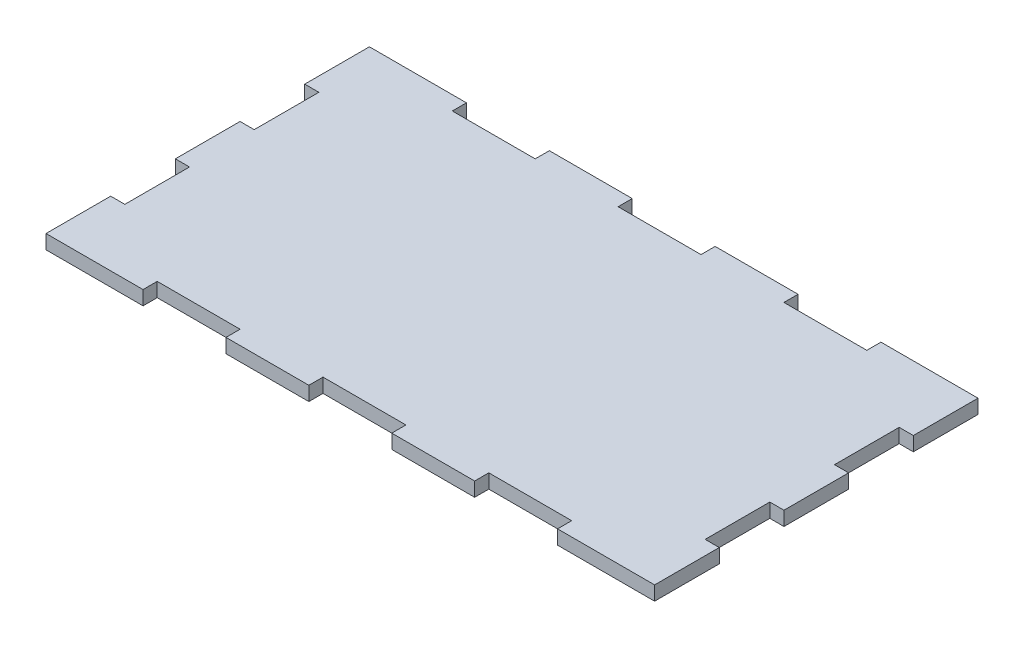
SolidWorks part; units mm, degrees
ref_plane "Front Plane" through (0, 0, 0) normal (0, 0, 1) x (1, 0, 0)
ref_plane "Top Plane" through (0, 0, 0) normal (0, 1, 0) x (1, 0, 0)
ref_plane "Right Plane" through (0, 0, 0) normal (1, 0, 0) x (0, 0, -1)
sketch "Sketch1" plane through (0, 0, 0) normal (0, 1, 0) x (1, 0, 0)
  line L1 (-215.1, 114.3) -> (-146.5, 114.3)
  line L2 (-215.1, 114.3) -> (-215.1, 68.58)
  line L4 (215.1, 114.3) -> (215.1, 68.58)
  line L5 (-215.1, -114.3) -> (-205.1, -114.3)
  line L6 (-205.1, -114.3) -> (-146.5, -114.3)
  line L7 (205.1, 68.58) -> (205.1, 22.86)
  line L9 (-205.1, 68.58) -> (-205.1, 22.86)
  line L11 (146.5, 104.3) -> (146.5, 114.3)
  line L12 (87.9, 104.3) -> (87.9, 114.3)
  line L13 (29.3, 104.3) -> (29.3, 114.3)
  line L14 (-29.3, 104.3) -> (-29.3, 114.3)
  line L15 (-87.9, 104.3) -> (-87.9, 114.3)
  line L16 (-146.5, 104.3) -> (-146.5, 114.3)
  line L17 (-215.1, -68.58) -> (-215.1, -114.3)
  line L18 (205.1, -22.86) -> (205.1, -68.58)
  line L20 (146.5, -104.3) -> (146.5, -114.3)
  line L21 (87.9, -104.3) -> (87.9, -114.3)
  line L22 (29.3, -104.3) -> (29.3, -114.3)
  line L23 (-29.3, -104.3) -> (-29.3, -114.3)
  line L24 (-87.9, -104.3) -> (-87.9, -114.3)
  line L25 (-146.5, -104.3) -> (-146.5, -114.3)
  line L26 (215.1, -114.3) -> (205.1, -114.3)
  line L27 (146.5, -114.3) -> (205.1, -114.3)
  line L28 (-205.1, -104.3) -> (205.1, -104.3) construction
  line L29 (87.9, -104.3) -> (146.5, -104.3)
  line L31 (-215.1, -114.3) -> (215.1, -114.3) construction
  line L32 (29.3, -114.3) -> (87.9, -114.3)
  line L33 (-29.3, -104.3) -> (29.3, -104.3)
  line L34 (-87.9, -114.3) -> (-29.3, -114.3)
  line L35 (-146.5, -104.3) -> (-87.9, -104.3)
  line L36 (215.1, -68.58) -> (205.1, -68.58)
  line L37 (215.1, -22.86) -> (205.1, -22.86)
  line L38 (-205.1, 104.3) -> (205.1, 104.3) construction
  line L39 (146.5, 114.3) -> (215.1, 114.3)
  line L40 (-215.1, 114.3) -> (215.1, 114.3) construction
  line L41 (29.3, 114.3) -> (87.9, 114.3)
  line L42 (-87.9, 114.3) -> (-29.3, 114.3)
  line L43 (-146.5, 104.3) -> (-87.9, 104.3)
  line L44 (-29.3, 104.3) -> (29.3, 104.3)
  line L45 (87.9, 104.3) -> (146.5, 104.3)
  line L46 (215.1, 22.86) -> (205.1, 22.86)
  line L47 (215.1, 68.58) -> (205.1, 68.58)
  line L48 (-215.1, -68.58) -> (-205.1, -68.58)
  line L49 (-215.1, -22.86) -> (-205.1, -22.86)
  line L50 (-215.1, 22.86) -> (-205.1, 22.86)
  line L51 (-215.1, 68.58) -> (-205.1, 68.58)
  line L52 (-205.1, 104.3) -> (-205.1, -104.3) construction
  line L53 (-205.1, -22.86) -> (-205.1, -68.58)
  line L54 (-215.1, 114.3) -> (-215.1, -114.3) construction
  line L55 (-215.1, 22.86) -> (-215.1, -22.86)
  line L56 (205.1, 104.3) -> (205.1, -104.3) construction
  line L57 (215.1, 22.86) -> (215.1, -22.86)
  line L58 (215.1, 114.3) -> (215.1, -114.3) construction
  line L59 (215.1, -68.58) -> (215.1, -114.3)
  point P0 (0, 0)
  dimension "D1" = 430.2
  dimension "D2" = 228.6
  dimension "D6" = 5
  dimension "D7" = 5
  dimension "D3" = 10
extrude "Boss-Extrude1" add sketch "Sketch1" along normal blind 10
